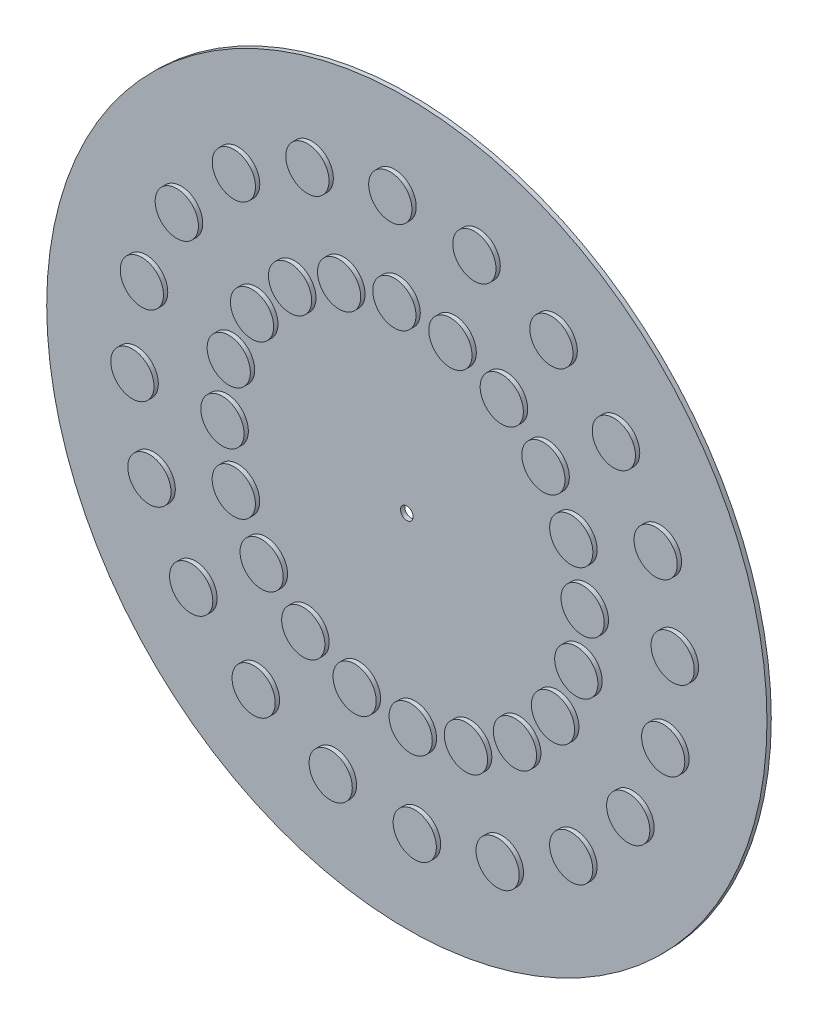
SolidWorks part; units mm, degrees
ref_plane "Front Plane" through (0, 0, 0) normal (0, 0, 1) x (1, 0, 0)
ref_plane "Top Plane" through (0, 0, 0) normal (0, 1, 0) x (1, 0, 0)
ref_plane "Right Plane" through (0, 0, 0) normal (1, 0, 0) x (0, 0, -1)
sketch "Sketch1" plane through (0, 0, 0) normal (0, 0, 1) x (1, 0, 0)
  circle A0 centre (0, 0) radius 100
  circle A1 centre (0, 0) radius 1.75
  dimension "D1" = 3.5
  dimension "D2" = 200
extrude "Boss-Extrude1" add sketch "Sketch1" along normal blind 1.2
sketch "Sketch2" plane through (0, 0, 1.2) normal (0, 0, 1) x (1, 0, 0)
  line L0 (0, 0) -> (-3.396, 75) construction
  line L1 (0, 0) -> (19.9464, 72.3787) construction
  line L2 (0, 0) -> (41.3364, 62.6724) construction
  line L3 (0, 0) -> (58.6801, 46.8313) construction
  line L4 (0, 0) -> (70.2798, 26.4061) construction
  line L5 (0, 0) -> (75, 3.396) construction
  line L6 (0, 0) -> (72.3787, -19.9464) construction
  line L7 (0, 0) -> (62.6724, -41.3364) construction
  line L8 (0, 0) -> (46.8313, -58.6801) construction
  line L9 (0, 0) -> (26.4061, -70.2798) construction
  line L10 (0, 0) -> (3.396, -75) construction
  line L11 (0, 0) -> (-19.9464, -72.3787) construction
  line L12 (0, 0) -> (-41.3364, -62.6724) construction
  line L13 (0, 0) -> (-58.6801, -46.8313) construction
  line L14 (0, 0) -> (-70.2798, -26.4061) construction
  line L15 (0, 0) -> (-75, -3.396) construction
  line L16 (0, 0) -> (-72.3787, 19.9464) construction
  line L17 (0, 0) -> (-62.6724, 41.3364) construction
  line L18 (0, 0) -> (-46.8313, 58.6801) construction
  line L19 (0, 0) -> (-26.4061, 70.2798) construction
  circle A0 centre (-3.396, 75) radius 6
  circle A1 centre (19.9464, 72.3787) radius 6
  circle A2 centre (41.3364, 62.6724) radius 6
  circle A3 centre (58.6801, 46.8313) radius 6
  circle A4 centre (70.2798, 26.4061) radius 6
  circle A5 centre (75, 3.396) radius 6
  circle A6 centre (72.3787, -19.9464) radius 6
  circle A7 centre (62.6724, -41.3364) radius 6
  circle A8 centre (46.8313, -58.6801) radius 6
  circle A9 centre (26.4061, -70.2798) radius 6
  circle A10 centre (3.396, -75) radius 6
  circle A11 centre (-19.9464, -72.3787) radius 6
  circle A12 centre (-41.3364, -62.6724) radius 6
  circle A13 centre (-58.6801, -46.8313) radius 6
  circle A14 centre (-70.2798, -26.4061) radius 6
  circle A15 centre (-75, -3.396) radius 6
  circle A16 centre (-72.3787, 19.9464) radius 6
  circle A17 centre (-62.6724, 41.3364) radius 6
  circle A18 centre (-46.8313, 58.6801) radius 6
  circle A19 centre (-26.4061, 70.2798) radius 6
  circle A20 centre (-2.264, 50) radius 6
  circle A21 centre (13.2976, 48.2524) radius 6
  circle A22 centre (27.5576, 41.7816) radius 6
  circle A23 centre (39.1201, 31.2209) radius 6
  circle A24 centre (46.8532, 17.6041) radius 6
  circle A25 centre (50, 2.264) radius 6
  circle A26 centre (48.2524, -13.2976) radius 6
  circle A27 centre (41.7816, -27.5576) radius 6
  circle A28 centre (31.2209, -39.1201) radius 6
  circle A29 centre (17.6041, -46.8532) radius 6
  circle A30 centre (2.264, -50) radius 6
  circle A31 centre (-13.2976, -48.2524) radius 6
  circle A32 centre (-27.5576, -41.7816) radius 6
  circle A33 centre (-39.1201, -31.2209) radius 6
  circle A34 centre (-46.8532, -17.6041) radius 6
  circle A35 centre (-50, -2.264) radius 6
  circle A36 centre (-48.2524, 13.2976) radius 6
  circle A37 centre (-41.7816, 27.5576) radius 6
  circle A38 centre (-31.2209, 39.1201) radius 6
  circle A39 centre (-17.6041, 46.8532) radius 6
  point P24 (0, 0)
  point P64 (0, 0)
  point P105 (0, 0)
  dimension "D3" = 12
  dimension "D5" = 12
  dimension "D1" = 75
  dimension "D6" = 50
  dimension "D2" = 20
  dimension "D4" = 20
  dimension "D7" = 20
extrude "Boss-Extrude2" add sketch "Sketch2" along normal blind 1.2 contours A18 | A19 | A16 | A15 | A14 | A13 | A12 | A11 | A10 | A9 | A8 | A7 | A6 | A5 | A4 | A3 | A2 | A1 | A0 | A39 | A20 | A21 | A22 | A23 | A24 | A25 | A26 | A27 | A28 | A29 | A30 | A31 | A32 | A33 | A34 | A35 | A36 | A37 | A38 | A17
